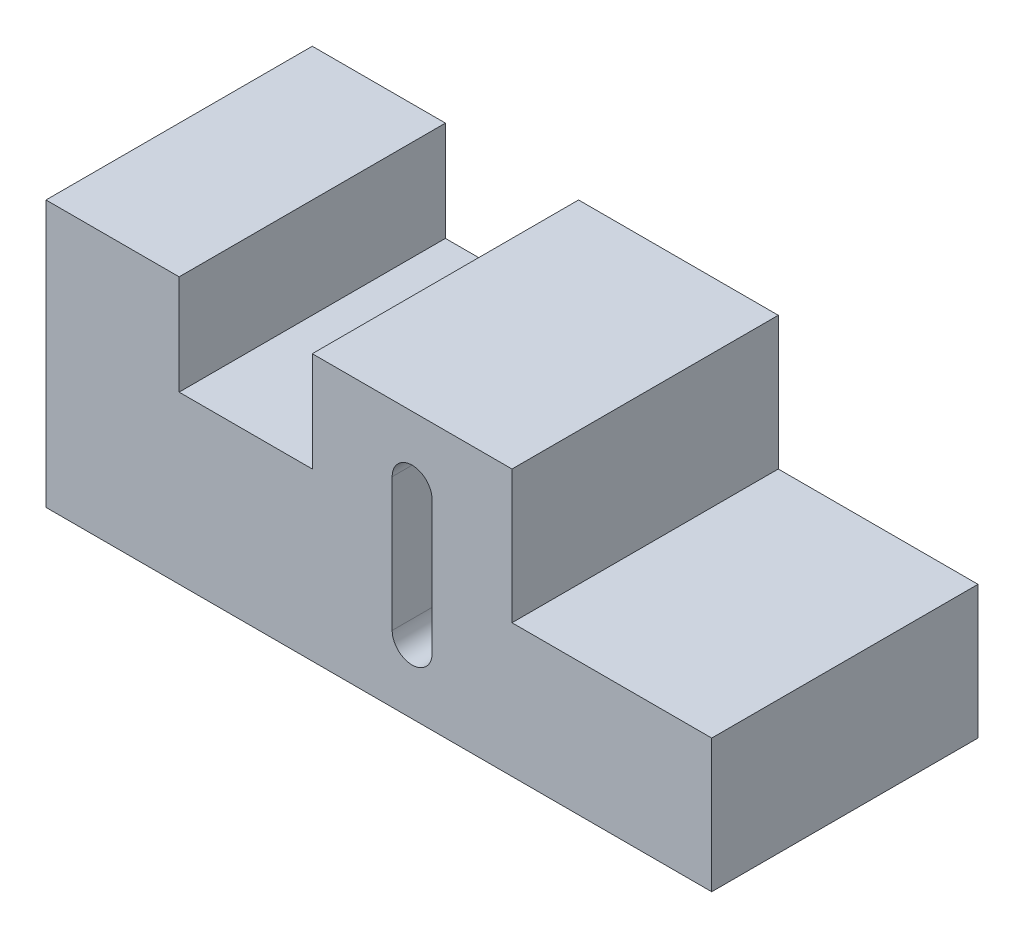
SolidWorks part; units mm, degrees
ref_plane "Front Plane" through (0, 0, 0) normal (0, 0, 1) x (1, 0, 0)
ref_plane "Top Plane" through (0, 0, 0) normal (0, 1, 0) x (1, 0, 0)
ref_plane "Right Plane" through (0, 0, 0) normal (1, 0, 0) x (0, 0, -1)
sketch "Sketch1" plane through (0, 0, 0) normal (0, 0, 1) x (1, 0, 0)
  line L0 (12.7, 25.4) -> (0, 25.4)
  line L1 (0, 25.4) -> (0, 0)
  line L2 (0, 0) -> (63.5, 0)
  line L3 (63.5, 0) -> (63.5, 12.7)
  line L4 (63.5, 12.7) -> (44.45, 12.7)
  line L5 (44.45, 12.7) -> (44.45, 25.4)
  line L6 (44.45, 25.4) -> (25.4, 25.4)
  line L7 (25.4, 25.4) -> (25.4, 15.875)
  line L8 (25.4, 15.875) -> (12.7, 15.875)
  line L9 (12.7, 15.875) -> (12.7, 25.4)
  line L10 (34.925, 25.4) -> (34.925, 0) construction
  line L11 (34.925, 19.05) -> (34.925, 6.35) construction
  line L12 (36.83, 19.05) -> (36.83, 6.35)
  line L13 (33.02, 19.05) -> (33.02, 6.35)
  arc A0 (36.83, 19.05) -> (33.02, 19.05) centre (34.925, 19.05) ccw
  arc A1 (33.02, 6.35) -> (36.83, 6.35) centre (34.925, 6.35) ccw
  point P15 (34.925, 12.7)
  dimension "D9" = 3.81
  dimension "D1" = 63.5
  dimension "D2" = 25.4
  dimension "D3" = 12.7
  dimension "D4" = 12.7
  dimension "D5" = 19.05
  dimension "D6" = 9.525
  dimension "D7" = 90
  dimension "D8" = 12.7
  dimension "D10" = 12.7
extrude "Boss-Extrude1" add sketch "Sketch1" against normal blind 25.4
ref_plane "Plane1" through (0, 25.4, 0) normal (0, 1, 0) x (-1, 0, 0)
sketch "Sketch2" plane through (0, 25.4, 0) normal (0, 1, 0) x (-1, 0, 0)
  line L0 (-44.45, -12.7) -> (-25.4, -12.7)
  line L1 (-44.45, -25.4) -> (-44.45, 0) construction
  line L2 (-25.4, -25.4) -> (-25.4, 0) construction
  dimension "Thickness" = 1.6002
